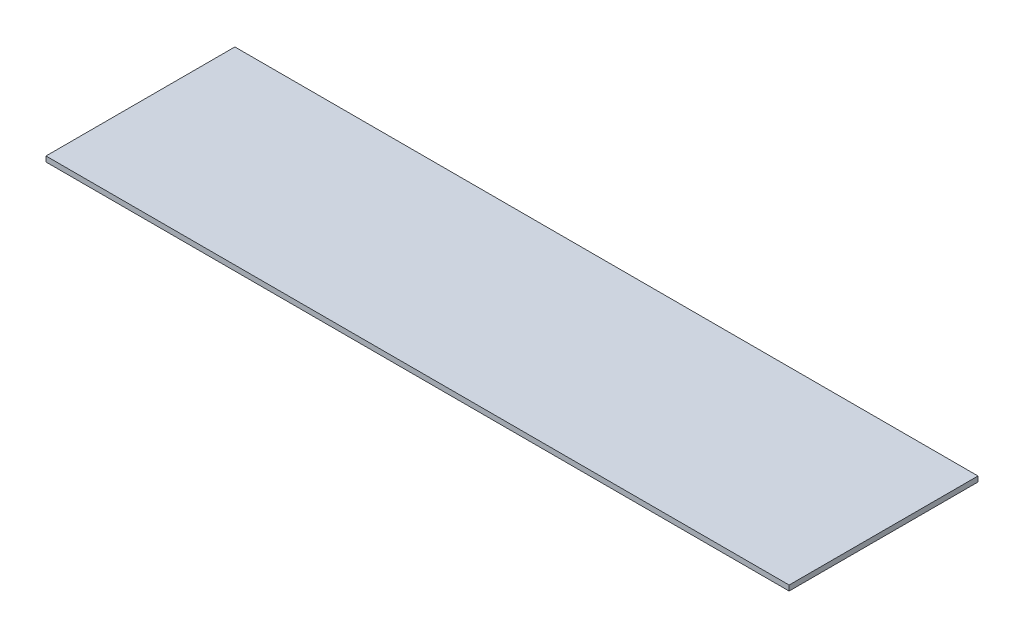
SolidWorks part; units mm, degrees
material "7075-T6 (SN)"
ref_plane "Front Plane" through (0, 0, 0) normal (0, 0, 1) x (1, 0, 0)
ref_plane "Top Plane" through (0, 0, 0) normal (0, 1, 0) x (1, 0, 0)
ref_plane "Right Plane" through (0, 0, 0) normal (1, 0, 0) x (0, 0, -1)
sketch "Sketch1" plane through (0, 0, 0) normal (0, 1, 0) x (1, 0, 0)
  line L1 (162.5, -41.3) -> (-162.5, -41.3)
  line L2 (162.5, -41.3) -> (162.5, 41.3)
  line L3 (162.5, 41.3) -> (-162.5, 41.3)
  line L4 (-162.5, -41.3) -> (-162.5, 41.3)
  line L5 (162.5, -41.3) -> (-162.5, 41.3) construction
  line L6 (162.5, 41.3) -> (-162.5, -41.3) construction
  point P0 (0, 0)
  dimension "D1" = 82.6
  dimension "D2" = 325
extrude "Boss-Extrude1" add sketch "Sketch1" along normal blind 2.3
ref_plane "Plane1" through (0, 0, 0) normal (0, 0, 1) x (1, 0, 0)
